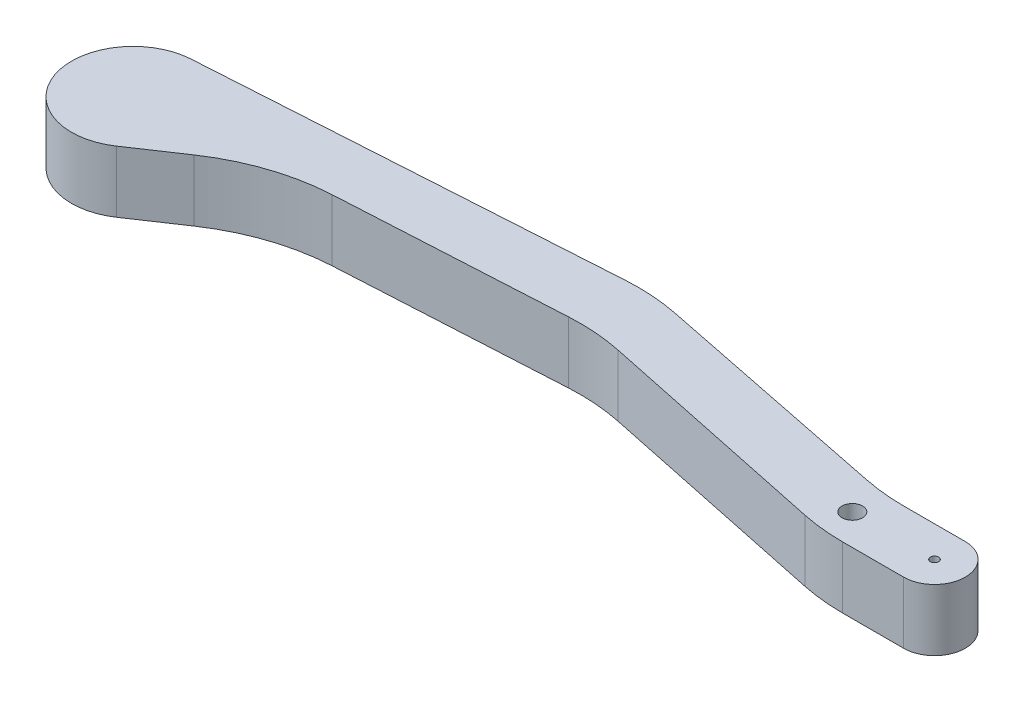
SolidWorks part; units mm, degrees
ref_plane "Front Plane" through (0, 0, 0) normal (0, 0, 1) x (1, 0, 0)
ref_plane "Top Plane" through (0, 0, 0) normal (0, 1, 0) x (1, 0, 0)
ref_plane "Right Plane" through (0, 0, 0) normal (1, 0, 0) x (0, 0, -1)
sketch "Sketch1" plane through (0, 0, 0) normal (0, 1, 0) x (1, 0, 0)
  line L0 (0, 0) -> (-350, 0) construction
  line L1 (0, 0) -> (40, 0) construction
  line L2 (0, 15) -> (40, 15)
  line L3 (0, -15) -> (40, -15)
  line L4 (-351.8754, 29.9413) -> (-333.2857, -24.9125) construction
  line L5 (-139.7849, 43.2259) -> (-4217.6379, -212.1962)
  line L6 (0, 15) -> (-4004.6012, 823.6244)
  line L7 (0, 15) -> (-5.9197, -13.7825) construction
  line L8 (-4217.6379, -212.1962) -> (-138.0533, 13.889)
  line L9 (-4004.6012, 823.6244) -> (-5.9197, -13.7825)
  line L10 (-333.2857, -24.9125) -> (-287.8235, 5.5889)
  line L11 (-5.9197, -13.7825) -> (0, -15)
  circle A0 centre (0, 0) radius 5
  circle A1 centre (-350, 0) radius 30
  circle A2 centre (40, 0) radius 2
  circle A3 centre (0, 0) radius 15
  circle A4 centre (40, 0) radius 15
  dimension "D1" = 10
  dimension "D4" = 4
  dimension "D5" = 60
  dimension "D6" = 30
  dimension "D7" = 165
  dimension "D2" = 350
  dimension "D3" = 40
  dimension "D8" = 165
  dimension "D9" = 135
  dimension "D10" = 150
extrude "Boss-Extrude1" add sketch "Sketch1" along normal blind 30 contours L8 A1 | A1 L8 | A1 L8 L9 L5 | A1 L10 L8 | A3 L6 L5 L9 | A3 A0 | A4 L2 A3 L3 | A4 A2
fillet "Fillet1" radius 100 5 edges at (0, 15, -15) (-139.7849, 15, -43.2259) (-138.0533, 15, -13.889) (-287.8235, 15, -5.5889) (0, 15, 15)
ref_plane "Plane1" through (-86.3568, 0, -128.7144) normal (0.5571, 0, 0.8304) x (0.8304, 0, -0.5571)
